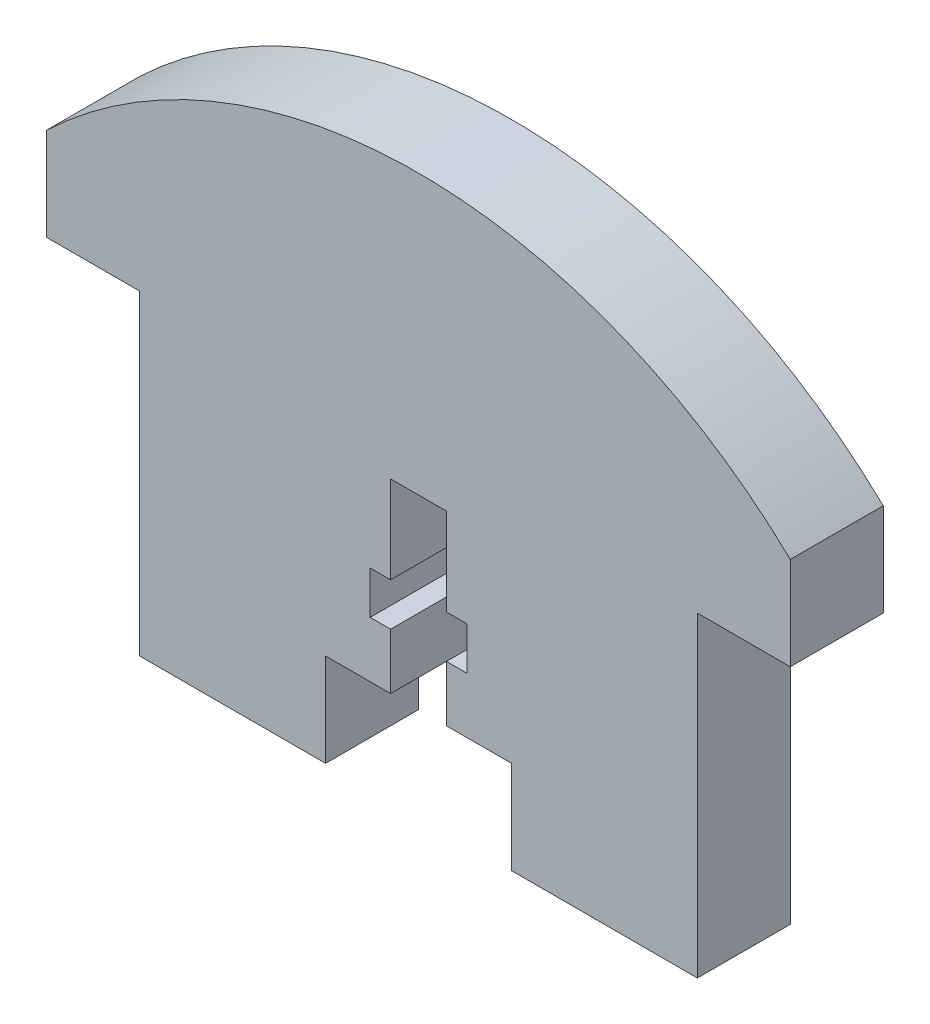
SolidWorks part; units mm, degrees
ref_plane "Plan de face" through (0, 0, 0) normal (0, 0, 1) x (1, 0, 0)
ref_plane "Plan de dessus" through (0, 0, 0) normal (0, 1, 0) x (1, 0, 0)
ref_plane "Plan de droite" through (0, 0, 0) normal (1, 0, 0) x (0, 0, -1)
sketch "Esquisse1" plane through (0, 0, 0) normal (0, 0, 1) x (1, 0, 0)
  line L1 (-15, 12) -> (-20, 12)
  line L2 (-20, 12) -> (-20, 17)
  line L3 (-20, 17) -> (20, 17) construction
  line L4 (20, 17) -> (20, 12)
  line L5 (20, 12) -> (15, 12)
  line L14 (0, 0) -> (0, 17) construction
  line L15 (15, 12) -> (15, 0)
  line L16 (-15, 12) -> (-15, 0)
  arc A0 (-20, 17) -> (20, 17) centre (0, -4) cw
  point P10 (0, 25)
  point P11 (0, 0)
  point P12 (20, 1.4802)
  point P13 (15, 1.6881)
  point P14 (0, 0)
  point P17 (0, 17)
  line B0 (-2.6, 3) -> (-2.6, 5.3)
  line B1 (1.5, 5.3) -> (1.5, 10)
  line B2 (-1.5, 10) -> (-1.5, 5.3)
  line B3 (-2.6, 5.3) -> (-1.5, 5.3)
  line B4 (0, 0) -> (0, 11.2208) construction
  line B5 (-1.5, 0) -> (-5, 0)
  line B6 (-5, -5) -> (-15, -5)
  line B7 (-15, -5) -> (-15, 0)
  line B8 (-5, -5) -> (-5, 0)
  line B9 (1.5, 0) -> (5, 0)
  line B10 (5, 0) -> (5, -5)
  line B11 (5, -5) -> (15, -5)
  line B12 (15, -5) -> (15, 0)
  line B13 (-1.5, 0) -> (1.5, 0) construction
  line B14 (1.5, 0) -> (1.5, 3)
  line B15 (1.5, 5.3) -> (2.6, 5.3)
  line B16 (2.6, 3) -> (1.5, 3)
  line B17 (1.5, 10) -> (-1.5, 10)
  line B18 (-1.5, 3) -> (-2.6, 3)
  line B19 (2.6, 5.3) -> (2.6, 3)
  line B20 (-1.5, 3) -> (-1.5, 0)
  line B21 (0, 10) -> (0, 0) construction
  dimension "D1" = 12
  dimension "D2" = 8
  dimension "D3" = 5
  dimension "D4" = 5
sketch_block_instance "Insert M3 plots ep 5mm-1"
sketch_block "Insert M3 plots ep 5mm" parameters "D1"=10, "D2"=10, "D3"=5
sketch_block_instance "Decoupe Insert M3-4"
sketch_block "Decoupe Insert M3" parameters "D1"=5.2, "D2"=3, "D3"=2.3, "D4"=3, "D5"=10
extrude "Boss.-Extru.1" add sketch "Esquisse1" along normal blind 5 contours B20 B18 B0 B3 B2 B17 B1 B15 B19 B16 B14 B9 B10 B11 B12 L15 L5 L4 A0 L2 L1 L16 B7 B6 B8 B5
